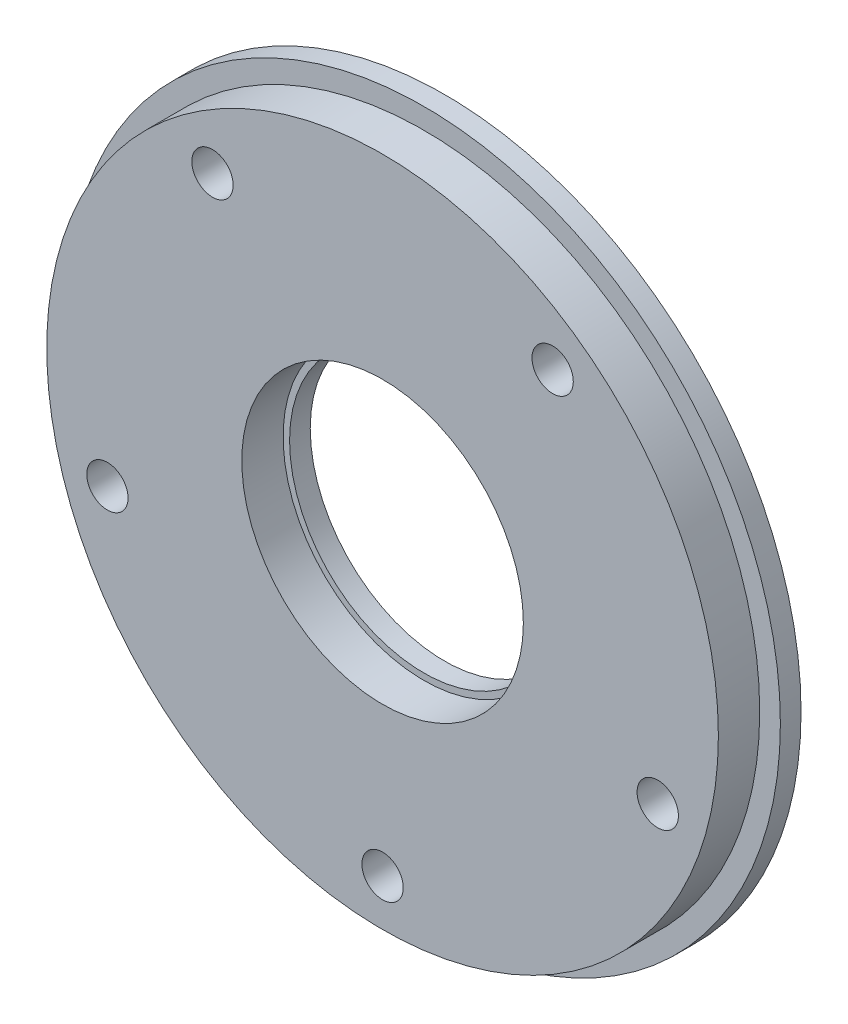
SolidWorks part; units mm, degrees
ref_plane "前视基准面" through (0, 0, 0) normal (0, 0, 1) x (1, 0, 0)
ref_plane "上视基准面" through (0, 0, 0) normal (0, 1, 0) x (1, 0, 0)
ref_plane "右视基准面" through (0, 0, 0) normal (1, 0, 0) x (0, 0, -1)
sketch "草图1" plane through (0, 0, 0) normal (0, 0, 1) x (1, 0, 0)
  line L0 (0, 0) -> (0, -28) construction
  circle A0 centre (0, 0) radius 13
  circle A1 centre (0, 0) radius 34.5
  circle A2 centre (0, -28) radius 2
  circle A3 centre (-26.6296, -8.6525) radius 2
  circle A4 centre (-16.458, 22.6525) radius 2
  circle A5 centre (16.458, 22.6525) radius 2
  circle A6 centre (26.6296, -8.6525) radius 2
  dimension "D1" = 26
  dimension "D2" = 69
  dimension "D4" = 4
  dimension "D3" = 28
  dimension "D5" = 5
extrude "凸台-拉伸1" add sketch "草图1" along normal blind 2 contours A1
sketch "草图2" plane through (0, 0, 2) normal (0, 0, 1) x (1, 0, 0)
  circle A0 centre (0, 0) radius 32.5
  circle A1 centre (0, 0) radius 13.625
  circle A2 centre (0, -28) radius 2
  circle A3 centre (-26.6296, -8.6525) radius 2
  circle A4 centre (-16.458, 22.6525) radius 2
  circle A5 centre (16.458, 22.6525) radius 2
  circle A6 centre (26.6296, -8.6525) radius 2
  dimension "D1" = 65
  dimension "D2" = 5
extrude "凸台-拉伸2" add sketch "草图2" along normal blind 4
